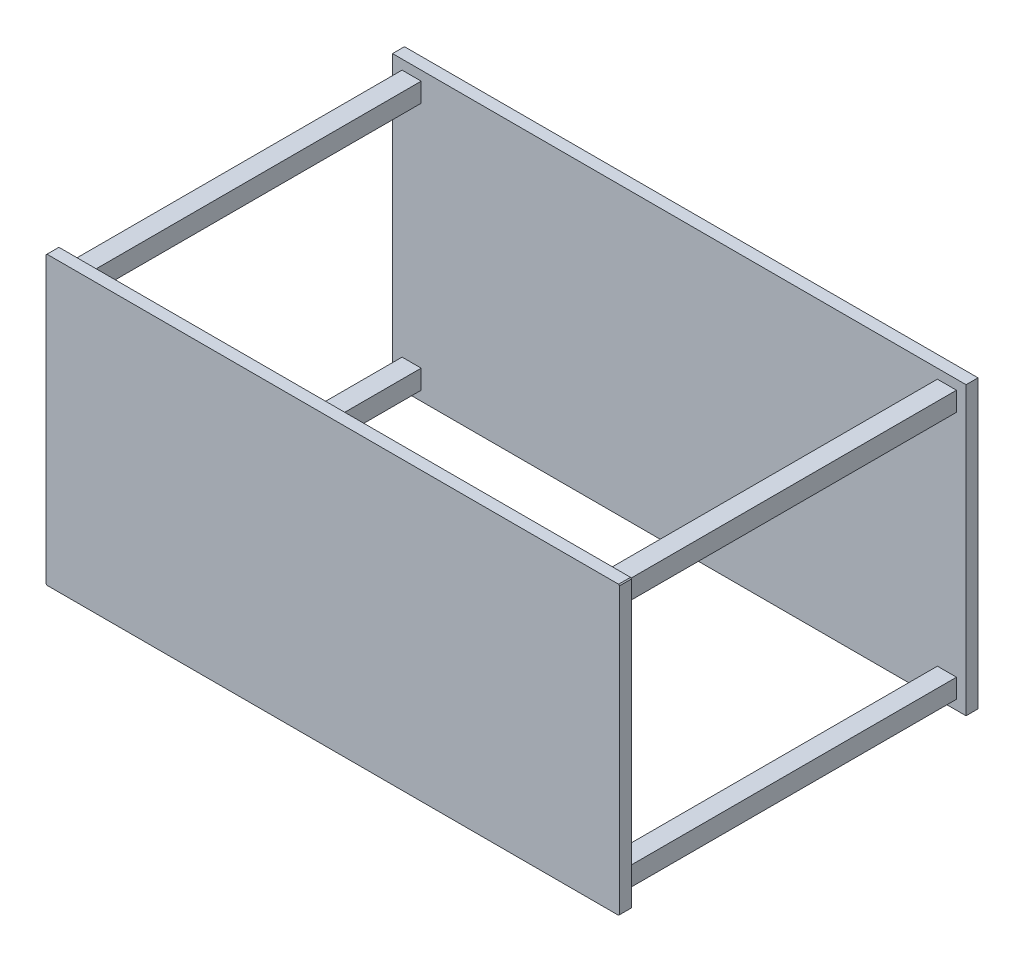
SolidWorks part; units mm, degrees
ref_plane "前视基准面" through (0, 0, 0) normal (0, 0, 1) x (1, 0, 0)
ref_plane "上视基准面" through (0, 0, 0) normal (0, 1, 0) x (1, 0, 0)
ref_plane "右视基准面" through (0, 0, 0) normal (1, 0, 0) x (0, 0, -1)
other "Configuration Table"
sketch "Sketch1" plane through (0, 0, 0) normal (0, 0, 1) x (1, 0, 0)
  line L1 (-600, -300) -> (600, -300)
  line L2 (-600, -300) -> (-600, 300)
  line L3 (-600, 300) -> (600, 300)
  line L4 (600, -300) -> (600, 300)
  line L5 (-600, -300) -> (600, 300) construction
  line L6 (-600, 300) -> (600, -300) construction
  point P0 (0, 0)
extrude "Boss-Extrude1" add sketch "Sketch1" along normal blind 25
sketch "Sketch2" plane through (0, 0, 0) normal (0, 0, 1) x (1, 0, 0)
  line L1 (-580, -280) -> (-540, -280)
  line L2 (-580, -280) -> (-580, -240)
  line L3 (-580, -240) -> (-540, -240)
  line L4 (-540, -280) -> (-540, -240)
  line L5 (-580, -280) -> (-540, -240) construction
  line L6 (-580, -240) -> (-540, -280) construction
  line L7 (540, -280) -> (580, -280)
  line L8 (540, -280) -> (540, -240)
  line L9 (540, -240) -> (580, -240)
  line L10 (580, -280) -> (580, -240)
  line L11 (540, -280) -> (580, -240) construction
  line L12 (540, -240) -> (580, -280) construction
  line L13 (540, 240) -> (580, 240)
  line L14 (540, 240) -> (540, 280)
  line L15 (540, 280) -> (580, 280)
  line L16 (580, 240) -> (580, 280)
  line L17 (540, 240) -> (580, 280) construction
  line L18 (540, 280) -> (580, 240) construction
  line L19 (-580, 240) -> (-540, 240)
  line L20 (-580, 240) -> (-580, 280)
  line L21 (-580, 280) -> (-540, 280)
  line L22 (-540, 240) -> (-540, 280)
  line L23 (-580, 240) -> (-540, 280) construction
  line L24 (-580, 280) -> (-540, 240) construction
  point P0 (-560, -260)
  point P5 (560, -260)
  point P10 (560, 260)
  point P15 (-560, 260)
extrude "Boss-Extrude2" add sketch "Sketch2" along normal blind 725
ref_plane "Plane1" through (0, 0, 725) normal (0, 0, 1) x (1, 0, 0)
sketch "Sketch3" plane through (0, 0, 725) normal (0, 0, 1) x (1, 0, 0)
  line L1 (-600, -300) -> (600, -300)
  line L2 (-600, -300) -> (-600, 300)
  line L3 (-600, 300) -> (600, 300)
  line L4 (600, -300) -> (600, 300)
  line L5 (-600, -300) -> (600, 300) construction
  line L6 (-600, 300) -> (600, -300) construction
  point P0 (0, 0)
extrude "Boss-Extrude3" add sketch "Sketch3" along normal blind 25
chamfer "Chamfer1" distance 2 angle 45 4 edges at (-600, -300, 737.5) (600, -300, 737.5) (-600, 300, 737.5) (600, 300, 737.5)
